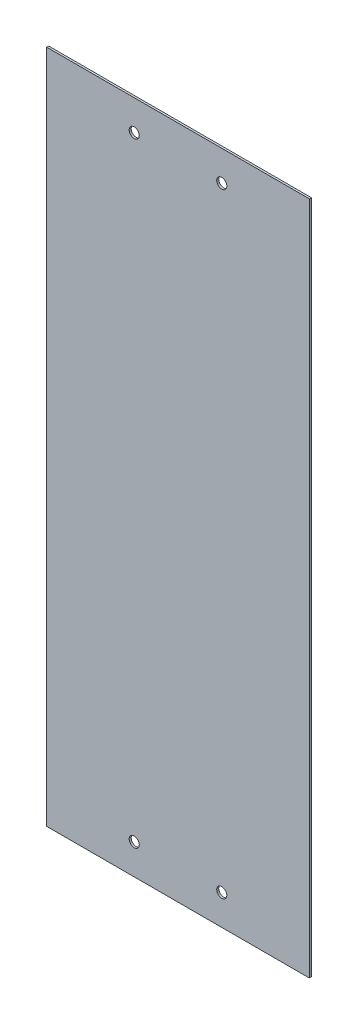
SolidWorks part; units mm, degrees
material "3.0526 (EN-AW 3005)"
ref_plane "Alzado" through (0, 0, 0) normal (0, 0, 1) x (1, 0, 0)
ref_plane "Planta" through (0, 0, 0) normal (0, 1, 0) x (1, 0, 0)
ref_plane "Vista lateral" through (0, 0, 0) normal (1, 0, 0) x (0, 0, -1)
sketch "Croquis1" plane through (0, 0, 0) normal (0, 0, 1) x (1, 0, 0)
  line L0 (-65, 167) -> (-65, 152)
  line L1 (65, -167) -> (-65, -167)
  line L2 (65, -167) -> (65, 167)
  line L3 (65, 167) -> (-65, 167)
  line L4 (-65, -167) -> (-65, 167)
  line L5 (65, -167) -> (-65, 167) construction
  line L6 (65, 167) -> (-65, -167) construction
  line L7 (-65, 152) -> (-21.6667, 152) construction
  line L8 (-21.6667, 152) -> (21.6667, 152) construction
  line L9 (0, 0) -> (85.9766, 0) construction
  circle A0 centre (-21.6667, 152) radius 2.5
  circle A1 centre (21.6667, 152) radius 2.5
  circle A2 centre (21.6667, -152) radius 2.5
  circle A3 centre (-21.6667, -152) radius 2.5
  point P0 (0, 0)
  dimension "D6" = 5
  dimension "D7" = 5
  dimension "D1" = 130
  dimension "D2" = 334
  dimension "D3" = 15
  dimension "D4" = 43.3333
  dimension "D5" = 43.3333
extrude "Saliente-Extruir1" add sketch "Croquis1" along normal blind 1 contours L4 L1 L2 L3 L0 A2 A1 A0 A3
